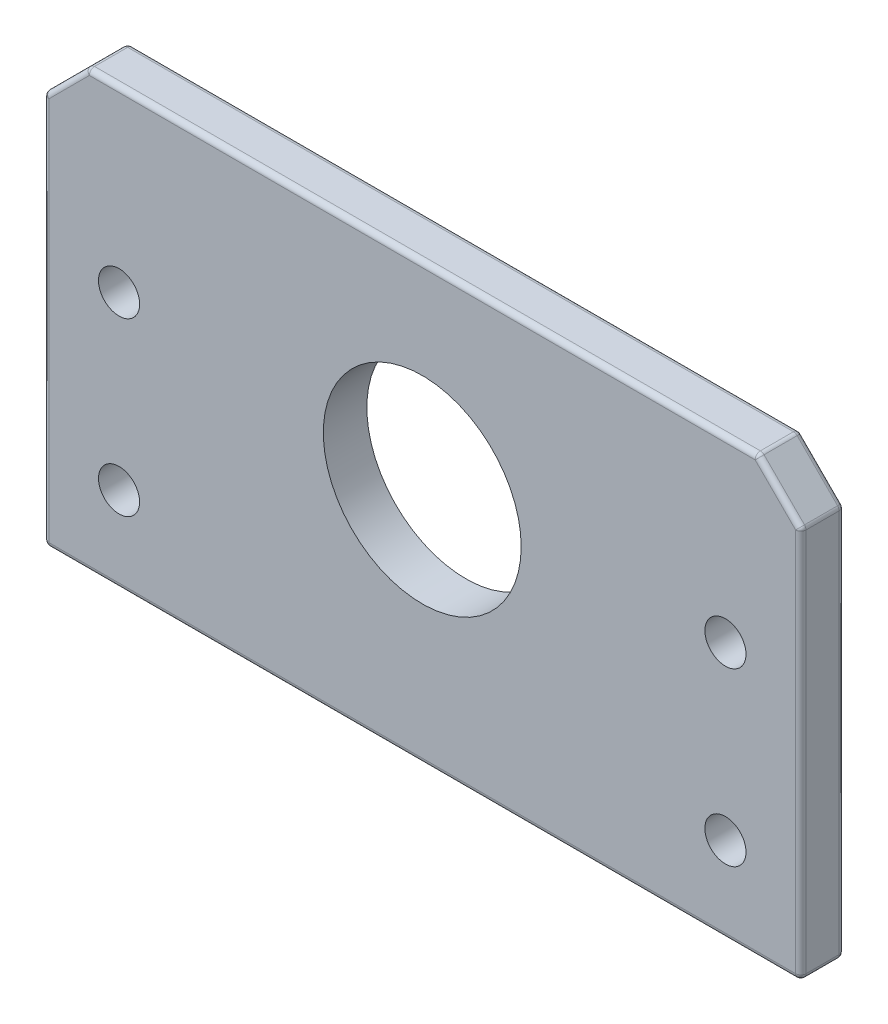
SolidWorks part; units mm, degrees
ref_plane "Front Plane" through (0, 0, 0) normal (0, 0, 1) x (1, 0, 0)
ref_plane "Top Plane" through (0, 0, 0) normal (0, 1, 0) x (1, 0, 0)
ref_plane "Right Plane" through (0, 0, 0) normal (1, 0, 0) x (0, 0, -1)
sketch "Sketch2" plane through (0, 0, 0) normal (0, 1, 0) x (1, 0, 0)
  line L1 (-55.245, 3.175) -> (55.245, 3.175)
  line L2 (-55.245, 3.175) -> (-55.245, -3.175)
  line L3 (-55.245, -3.175) -> (55.245, -3.175)
  line L4 (55.245, 3.175) -> (55.245, -3.175)
  point P4 (0, 3.175)
  point P7 (-55.245, 0)
  dimension "D1" = 6.35
  dimension "D2" = 110.49
extrude "Boss-Extrude1" add sketch "Sketch2" against normal blind 63.5
sketch "Sketch3" plane through (0, 0, 3.175) normal (0, 0, 1) x (1, 0, 0)
  line L2 (-55.245, 0) -> (55.245, 0) construction
  circle A0 centre (0, -28.815) radius 14.4375
  point P2 (0, 0)
  dimension "D1" = 28.815
  dimension "D3" = 28.875
extrude "Cut-Extrude1" cut sketch "Sketch3" against normal through all
chamfer "Chamfer1" distance 6.35 angle 45 2 edges at (-55.245, 0, 0) (55.245, 0, 0)
fillet "Fillet1" [suppressed] radius 0.762
hole_wizard "CBORE for M4 SHCS2" [suppressed] positions "Sketch9" profile "Sketch10" counterbore size "M4" standard "ANSI Metric"
sketch "Sketch9" [suppressed] plane through (0, 0, 3.175) normal (0, 0, 1) x (1, 0, 0)
  line L0 (-48.5794, 0) -> (48.5794, 0) construction
  line L1 (-55.245, -62.738) -> (-55.245, -6.6656) construction
  point P0 (-17.9605, -10.8545)
  dimension "D1" = 10.8545
  dimension "D2" = 37.2845
sketch "Sketch10" plane through (-17.9605, -10.8545, 3.175) normal (1, 0, 0) x (0, -1, 0)
  line L0 (0, 0) -> (0, 6.35)
  line L1 (0, 6.35) -> (2.25, 6.35)
  line L3 (2.25, 6.35) -> (2.25, 4)
  line L4 (2.25, 4) -> (4, 4)
  line L5 (4, 4) -> (4, 0)
  line L7 (4, 0) -> (0, 0)
  line L11 (0, -6.35) -> (0, 107.95) construction
  dimension "Thru Hole Dia." = 4.5
  dimension "Thru Hole Depth" = 6.35
  dimension "C'Bore Dia." = 8
  dimension "C'Bore Depth" = 4
sketch "Sketch12" plane through (0, 0, 3.175) normal (0, 0, 1) x (1, 0, 0)
  line L0 (-33.655, -49.5) -> (-33.655, -63.5)
  line L1 (-55.245, -63.5) -> (-55.245, -6.35) construction
  line L2 (-33.655, -63.5) -> (-18.655, -63.5)
  line L3 (-55.245, -63.5) -> (55.245, -63.5) construction
  line L5 (-18.655, -63.5) -> (-18.655, -49.5)
  arc A0 (-18.655, -49.5) -> (-33.655, -49.5) centre (-26.155, -49.5) ccw
  dimension "D4" = 7.5
  dimension "D1" = 14
  dimension "D2" = 15
  dimension "D3" = 14
  dimension "D5" = 29.09
extrude "Cut-Extrude2" [suppressed] cut sketch "Sketch12" against normal blind 1.524
mirror "Mirror1" [suppressed] about plane through (0, 0, 0) normal (1, 0, 0)
hole_wizard "Tap Drill for M4x0.7 Tap1" [suppressed] positions "Sketch13" profile "Sketch14" hole size "M4x0.7" standard "ANSI Metric"
sketch "Sketch13" plane through (0, 0, 3.175) normal (0, 0, 1) x (1, 0, 0)
  line L1 (0, -3.4925) -> (0, 3.4925) construction
  line L2 (-48.895, 0) -> (48.895, 0) construction
  point P0 (-26.155, -50)
  point P3 (26.155, -50)
  dimension "D1" = 52.31
  dimension "D2" = 26.155
  dimension "D3" = 50
sketch "Sketch14" plane through (-26.155, -50, 3.175) normal (1, 0, 0) x (0, -1, 0)
  line L0 (0, 0) -> (0, 6.35)
  line L1 (0, 6.35) -> (1.65, 6.35)
  line L2 (1.65, 6.35) -> (1.65, 0)
  line L5 (1.65, 0) -> (0, 0)
  line L11 (0, -6.35) -> (0, 107.95) construction
  dimension "Thru Hole Dia." = 3.3
  dimension "Thru Hole Depth" = 6.35
hole_wizard "Tap Drill for M7x1.0 Tap1" positions "Sketch17" profile "Sketch16" hole size "M7x1.0" standard "ANSI Metric" end condition through all
sketch "Sketch17" plane through (0, 0, -3.175) normal (0, 0, -1) x (-1, 0, 0)
  line L0 (0, 3.4925) -> (0, -3.4925) construction
  line L1 (-48.895, 0) -> (48.895, 0) construction
  point P0 (44.245, -26)
  point P3 (44.245, -51)
  point P6 (-44.245, -51)
  point P9 (-44.245, -26)
  dimension "D1" = 25
  dimension "D2" = 25
  dimension "D3" = 88.49
  dimension "D4" = 44.245
  dimension "D5" = 26
sketch "Sketch16" plane through (-44.245, -26, -3.175) normal (1, 0, 0) x (0, 1, 0)
  line L0 (0, 0) -> (0, 6.35)
  line L1 (0, 6.35) -> (3, 6.35)
  line L2 (3, 6.35) -> (3, 0)
  line L5 (3, 0) -> (0, 0)
  line L11 (0, -6.35) -> (0, 107.95) construction
  dimension "Thru Hole Dia." = 6
  dimension "Thru Hole Depth" = 6.35
fillet "Fillet2" radius 0.762 18 edges at (0, -63.5, 3.175) (0, -63.5, -3.175) (55.245, -63.5, 0) (55.245, -34.925, 3.175) (55.245, -34.925, -3.175) (52.07, -3.175, -3.175) (55.245, -6.35, 0) (52.07, -3.175, 3.175) (48.895, 0, 0) (0, 0, 3.175) (0, 0, -3.175) (-48.895, 0, 0) (-52.07, -3.175, 3.175) (-52.07, -3.175, -3.175) (-55.245, -63.5, 0) (-55.245, -34.925, -3.175) (-55.245, -6.35, 0) (-55.245, -34.925, 3.175)
